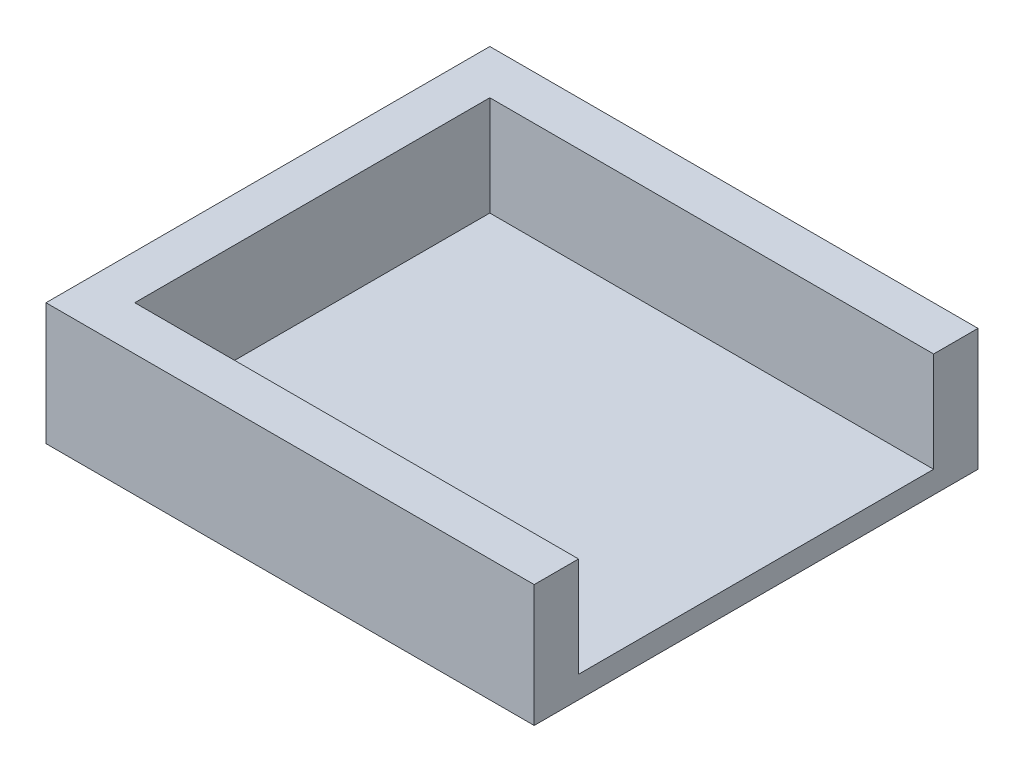
SolidWorks part; units mm, degrees
ref_plane "Front Plane" through (0, 0, 0) normal (0, 0, 1) x (1, 0, 0)
ref_plane "Top Plane" through (0, 0, 0) normal (0, 1, 0) x (1, 0, 0)
ref_plane "Right Plane" through (0, 0, 0) normal (1, 0, 0) x (0, 0, -1)
sketch "Sketch1" plane through (0, 0, 0) normal (0, 1, 0) x (1, 0, 0)
  line L0 (-110, -100) -> (-110, 100)
  line L1 (-90, -80) -> (110, -80)
  line L2 (-90, -80) -> (-90, 80)
  line L3 (-90, 80) -> (110, 80)
  line L5 (-90, -80) -> (90, 80) construction
  line L6 (-90, 80) -> (90, -80) construction
  line L7 (-110, 100) -> (110, 100)
  line L8 (110, -100) -> (110, -80)
  line L9 (-110, -100) -> (110, -100)
  line L10 (90, -80) -> (90, 80) construction
  line L11 (-90, 80) -> (90, 80) construction
  line L12 (-90, -80) -> (90, -80) construction
  line L13 (110, 80) -> (110, 100)
  line L14 (110, -100) -> (110, 100) construction
  point P0 (0, 0)
  dimension "D1" = 180
  dimension "D2" = 160
  dimension "D3" = 20
extrude "Boss-Extrude1" add sketch "Sketch1" along normal blind 45
sketch "Sketch2" plane through (0, 0, 0) normal (0, -1, 0) x (-1, 0, 0)
  line L1 (110, 100) -> (-110, 100)
  line L2 (110, 100) -> (110, -100)
  line L3 (110, -100) -> (-110, -100)
  line L4 (-110, 100) -> (-110, -100)
extrude "Boss-Extrude2" add sketch "Sketch2" along normal blind 10
